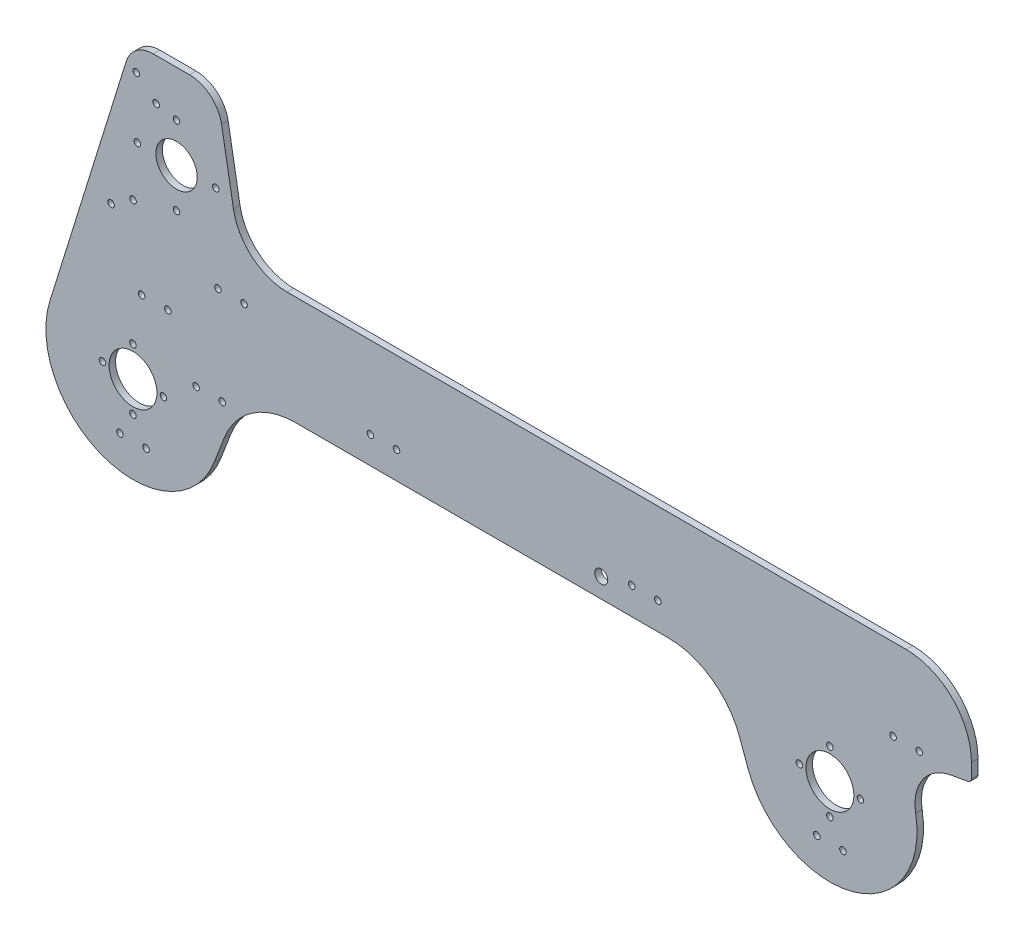
SolidWorks part; units mm, degrees
ref_plane "前视基准面" through (0, 0, 0) normal (0, 0, 1) x (1, 0, 0)
ref_plane "上视基准面" through (0, 0, 0) normal (0, 1, 0) x (1, 0, 0)
ref_plane "右视基准面" through (0, 0, 0) normal (1, 0, 0) x (0, 0, -1)
sketch "Model" plane through (0, 0, 0) normal (0, 0, 1) x (1, 0, 0)
  line L0 (1088.5087, 149.6726) -> (1083.0521, 180.6186)
  line L1 (1397.3576, 129.0138) -> (1113.1289, 129.0138)
  line L2 (1427.3576, 92.692) -> (1427.3576, 99.0138)
  line L3 (1417.9337, 89.3521) -> (1425.7049, 90.7224)
  line L4 (1401.7499, 65.9598) -> (1401.7105, 66.183)
  line L5 (1320.893, 55.9845) -> (1324.7699, 45.333)
  line L6 (1288.0038, 79.0138) -> (1116.9355, 79.0138)
  line L7 (1079.7008, 44.6791) -> (1084.2602, 56.5567)
  line L8 (1004.1586, 70.8815) -> (1039.2624, 183.8708)
  line L9 (1068.28, 193.0138) -> (1051.677, 193.0138)
  circle A0 centre (1362.3576, 59.0138) radius 11
  circle A1 centre (1042.3576, 59.0138) radius 11
  circle A2 centre (1062.3576, 154.0138) radius 9.5
  circle A3 centre (1151.3576, 91.5138) radius 1.5
  circle A4 centre (1163.3576, 91.5138) radius 1.5
  circle A5 centre (1271.3576, 91.5138) radius 1.5
  circle A6 centre (1283.3576, 91.5138) radius 1.5
  circle A7 centre (1391.3576, 91.5138) radius 1.5
  circle A8 centre (1403.3576, 91.5138) radius 1.5
  circle A9 centre (1093.3576, 114.5138) radius 1.5
  circle A10 centre (1081.3576, 114.5138) radius 1.5
  circle A11 centre (1046.3576, 94.5138) radius 1.5
  circle A12 centre (1058.3576, 94.5138) radius 1.5
  circle A13 centre (1071.3576, 70.5138) radius 1.5
  circle A14 centre (1083.3576, 70.5138) radius 1.5
  circle A15 centre (1036.3576, 34.5138) radius 1.5
  circle A16 centre (1048.3576, 34.5138) radius 1.5
  circle A17 centre (1356.3576, 34.5138) radius 1.5
  circle A18 centre (1368.3576, 34.5138) radius 1.5
  circle A19 centre (1062.3576, 172.0138) radius 1.5
  circle A20 centre (1080.3576, 154.0138) radius 1.5
  circle A21 centre (1062.3576, 136.0138) radius 1.5
  circle A22 centre (1044.3576, 154.0138) radius 1.5
  circle A23 centre (1042.3803, 130.3092) radius 1.5
  circle A24 centre (1032.3163, 123.7735) radius 1.5
  circle A25 centre (1042.3576, 73.0138) radius 1.5
  circle A26 centre (1056.3576, 59.0138) radius 1.5
  circle A27 centre (1042.3576, 45.0138) radius 1.5
  circle A28 centre (1028.3576, 59.0138) radius 1.5
  circle A29 centre (1362.3576, 73.0138) radius 1.5
  circle A30 centre (1376.3576, 59.0138) radius 1.5
  circle A31 centre (1362.3576, 45.0138) radius 1.5
  circle A32 centre (1348.3576, 59.0138) radius 1.5
  arc A33 (1004.1586, 70.8815) -> (1079.7008, 44.6791) centre (1042.3576, 59.0138) ccw
  arc A34 (1088.5087, 149.6726) -> (1113.1289, 129.0138) centre (1113.1289, 154.0138) ccw
  arc A35 (1427.3576, 99.0138) -> (1397.3576, 129.0138) centre (1397.3576, 99.0138) ccw
  arc A36 (1425.7049, 90.7224) -> (1427.3576, 92.692) centre (1425.3576, 92.692) ccw
  arc A37 (1417.9337, 89.3521) -> (1401.7105, 66.183) centre (1421.4067, 69.656) ccw
  arc A38 (1324.7699, 45.333) -> (1401.7499, 65.9598) centre (1362.3576, 59.0138) ccw
  arc A39 (1320.893, 55.9845) -> (1288.0038, 79.0138) centre (1288.0038, 44.0138) ccw
  arc A40 (1116.9355, 79.0138) -> (1084.2602, 56.5567) centre (1116.9355, 44.0138) ccw
  circle A41 centre (1257.3576, 88.0138) radius 3
  arc A42 (1083.0521, 180.6186) -> (1068.28, 193.0138) centre (1068.28, 178.0138) ccw
  circle A43 centre (1043.8859, 181.7) radius 1.5
  circle A44 centre (1052.997, 173.8906) radius 1.5
  arc A45 (1051.677, 193.0138) -> (1039.2624, 183.8708) centre (1051.677, 180.0138) ccw
  dimension "D1" = 3
extrude "凸台-拉伸1" add sketch "Model" along normal blind 3
